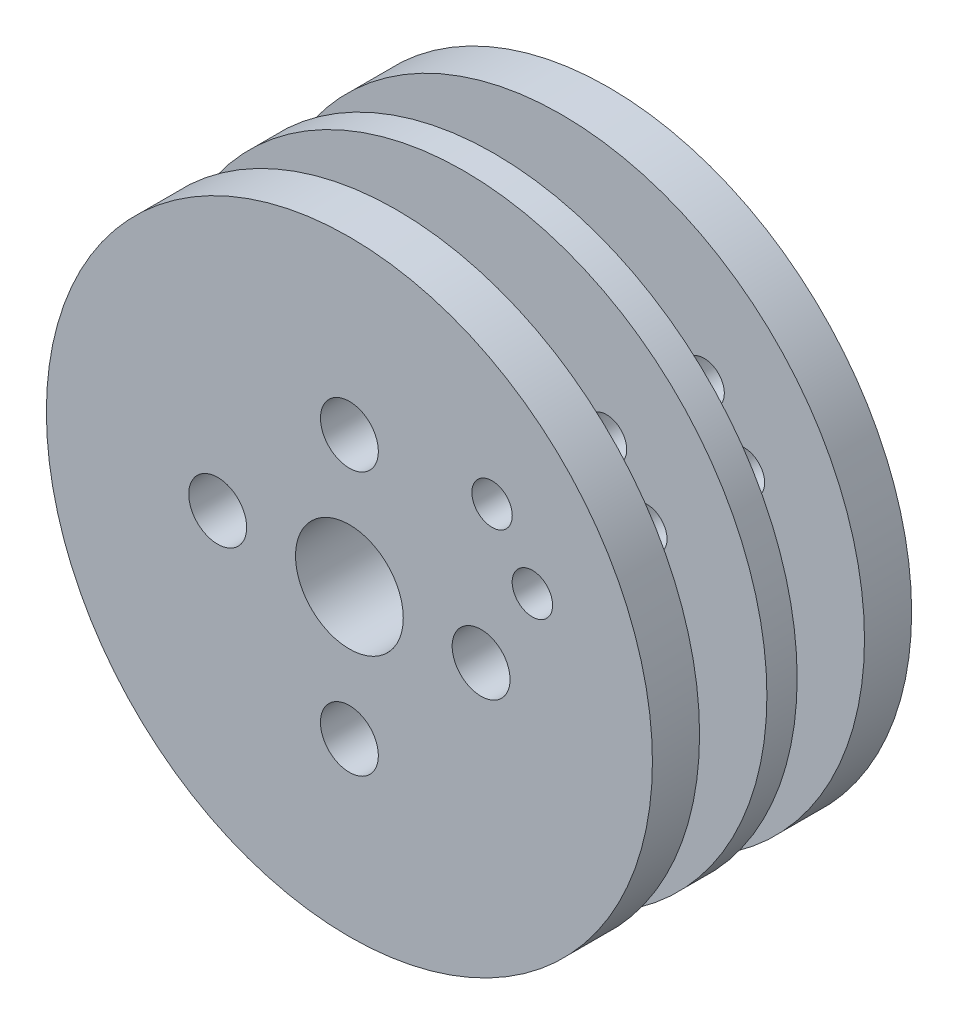
SolidWorks part; units mm, degrees
ref_plane "Front Plane" through (0, 0, 0) normal (0, 0, 1) x (1, 0, 0)
ref_plane "Top Plane" through (0, 0, 0) normal (0, 1, 0) x (1, 0, 0)
ref_plane "Right Plane" through (0, 0, 0) normal (1, 0, 0) x (0, 0, -1)
sketch "Sketch1" plane through (0, 0, 0) normal (0, 0, 1) x (1, 0, 0)
  circle A5 centre (0, 0) radius 22.5
  dimension "D1" = 45
extrude "Boss-Extrude1" add sketch "Sketch1" along normal blind 2.246
sketch "Sketch2" plane through (0, 0, 0) normal (0, 0, 1) x (1, 0, 0)
  circle A0 centre (0, 0) radius 13
  dimension "D1" = 26
extrude "Boss-Extrude2" add sketch "Sketch2" against normal blind 5
sketch "Sketch5" plane through (0, 0, -5) normal (0, 0, -1) x (-1, 0, 0)
  circle A2 centre (0, 0) radius 22.5
  circle A3 centre (0, 0) radius 22.5
  dimension "D1" = 0
extrude "Boss-Extrude4" add sketch "Sketch5" along normal blind 3.5
sketch "Sketch8" plane through (0, 0, 2.246) normal (0, 0, 1) x (1, 0, 0)
  circle A2 centre (0, 0) radius 13 construction
  circle A3 centre (0, 0) radius 13
extrude "Boss-Extrude5" add sketch "Sketch8" along normal blind 5
sketch "Sketch12" plane through (0, 0, 7.246) normal (0, 0, 1) x (1, 0, 0)
  circle A5 centre (0, 0) radius 22.5 construction
  circle A6 centre (0, 0) radius 22.5
extrude "Boss-Extrude6" add sketch "Sketch12" along normal blind 3.5
sketch "Sketch6" plane through (0, 0, 10.746) normal (0, 0, 1) x (1, 0, 0)
  line L0 (0, 0) -> (0, 9.779) construction
  circle A0 centre (0, 0) radius 4
  circle A1 centre (0, 9.779) radius 2.15
  circle A2 centre (9.779, 0) radius 2.15
  circle A3 centre (0, -9.779) radius 2.15
  circle A4 centre (-9.779, 0) radius 2.15
  circle A5 centre (0, 0) radius 13 construction
  circle A6 centre (0, 0) radius 13 construction
  circle A8 centre (10.5925, 10.6207) radius 1.5
  circle A10 centre (13.5862, 6.3573) radius 1.5
  point P14 (0, 0)
  point P21 (0, 0)
  dimension "D1" = 8
  dimension "D3" = 4.3
  dimension "D6" = 3
  dimension "D2" = 9.779
  dimension "D5" = 15
  dimension "D4" = 4
  dimension "D7" = 2
extrude "Cut-Extrude1" cut sketch "Sketch6" against normal through all
